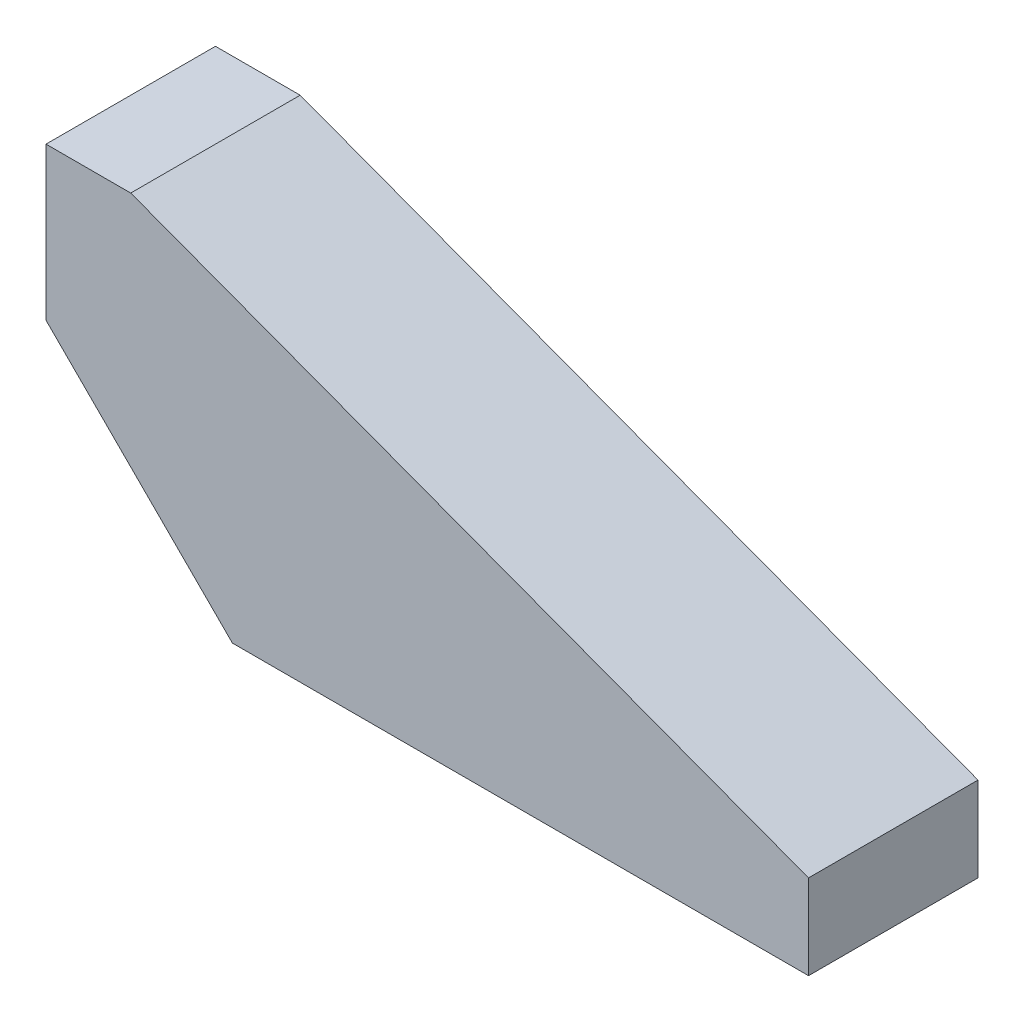
SolidWorks part; units mm, degrees
ref_plane "前视基准面" through (0, 0, 0) normal (0, 0, 1) x (1, 0, 0)
ref_plane "上视基准面" through (0, 0, 0) normal (0, 1, 0) x (1, 0, 0)
ref_plane "右视基准面" through (0, 0, 0) normal (1, 0, 0) x (0, 0, -1)
sketch "草图1" plane through (0, 0, 0) normal (0, 0, 1) x (1, 0, 0)
  line L0 (0, 0) -> (10, 0)
  line L1 (10, 0) -> (90, -30)
  line L2 (90, -30) -> (90, -40)
  line L3 (90, -40) -> (22, -40)
  line L4 (22, -40) -> (0, -18)
  line L5 (0, -18) -> (0, 0)
  dimension "D1" = 10
  dimension "D2" = 40
  dimension "D3" = 10
  dimension "D4" = 90
  dimension "D5" = 18
  dimension "D6" = 68
extrude "凸台-拉伸1" add sketch "草图1" along normal blind 20
